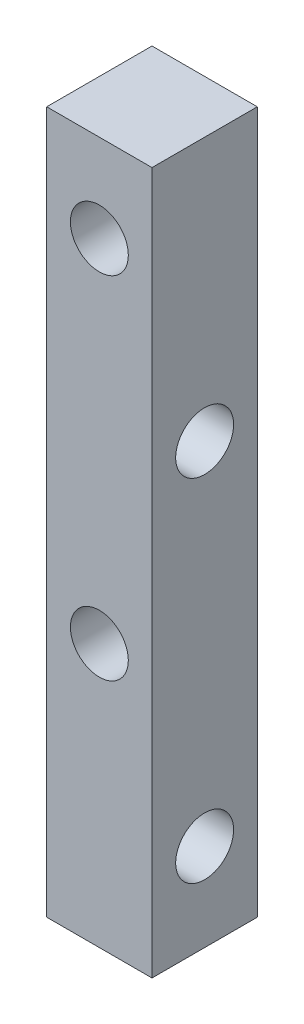
SolidWorks part; units mm, degrees
ref_plane "前视基准面" through (0, 0, 0) normal (0, 0, 1) x (1, 0, 0)
ref_plane "上视基准面" through (0, 0, 0) normal (0, 1, 0) x (1, 0, 0)
ref_plane "右视基准面" through (0, 0, 0) normal (1, 0, 0) x (0, 0, -1)
sketch "草图1" plane through (0, 0, 0) normal (0, 1, 0) x (1, 0, 0)
  line L1 (-3, 3) -> (3, 3)
  line L2 (-3, 3) -> (-3, -3)
  line L3 (-3, -3) -> (3, -3)
  line L4 (3, 3) -> (3, -3)
  line L5 (-3, 3) -> (3, -3) construction
  line L6 (-3, -3) -> (3, 3) construction
  point P0 (0, 0)
  dimension "D1" = 6
extrude "凸台-拉伸1" add sketch "草图1" along normal mid plane 40
sketch "草图3" plane through (0, 0, 3) normal (0, 0, 1) x (1, 0, 0)
  line L0 (-3, 20) -> (3, 20) construction
  circle A0 centre (0, 15) radius 1.65
  circle A1 centre (0, -5) radius 1.65
  dimension "D1" = 5
  dimension "D3" = 3.3
  dimension "D2" = 20
extrude "切除-拉伸1" cut sketch "草图3" against normal through all both and the other way through all
sketch "草图4" plane through (3, 0, 0) normal (1, 0, 0) x (0, 0, -1)
  line L0 (-3, -20) -> (3, -20) construction
  circle A0 centre (0, 5) radius 1.65
  circle A1 centre (0, -15) radius 1.65
  dimension "D1" = 3.3
  dimension "D2" = 20
  dimension "D3" = 5
extrude "切除-拉伸2" cut sketch "草图4" against normal through all both and the other way through all
